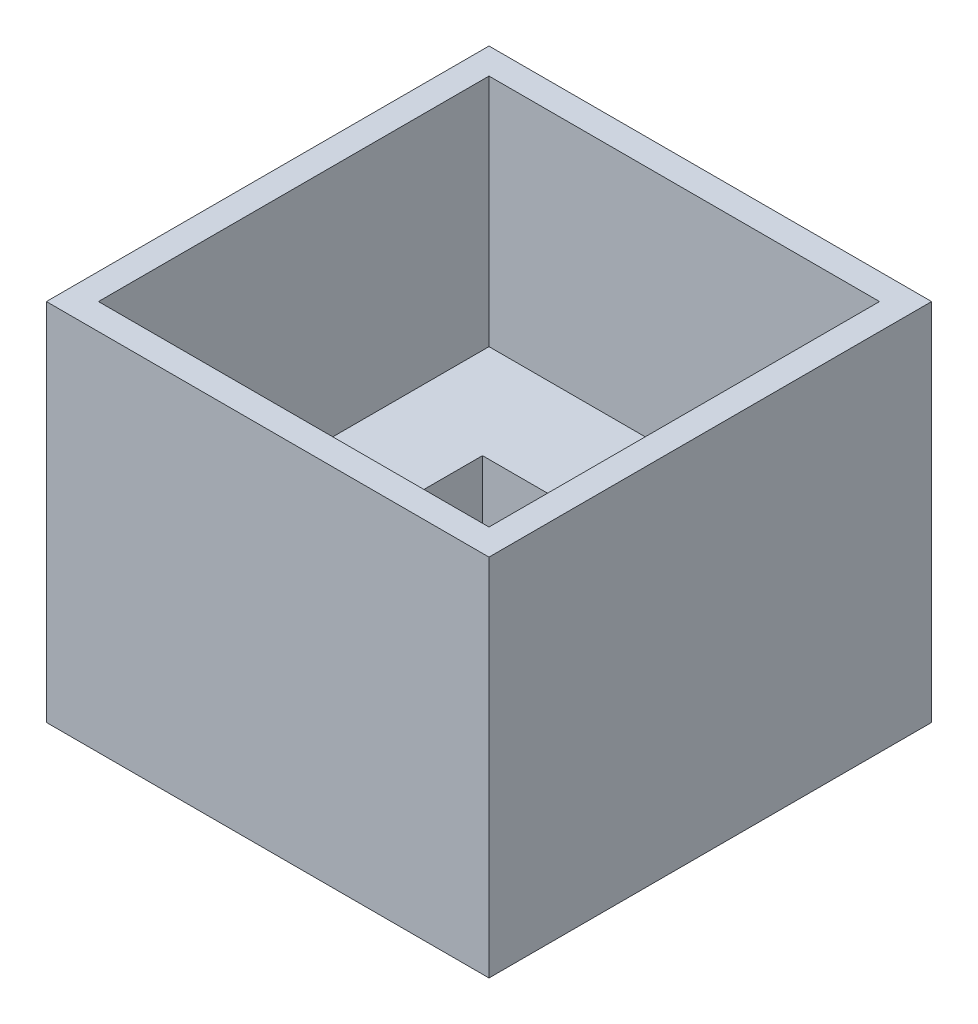
SolidWorks part; units mm, degrees
ref_plane "Front" through (0, 0, 0) normal (0, 0, 1) x (1, 0, 0)
ref_plane "Top" through (0, 0, 0) normal (0, 1, 0) x (1, 0, 0)
ref_plane "Right" through (0, 0, 0) normal (1, 0, 0) x (0, 0, -1)
sketch "Эскиз2" plane through (0, 0, 0) normal (0, 1, 0) x (1, 0, 0)
  line L1 (-85, -85) -> (85, -85)
  line L2 (-85, -85) -> (-85, 85)
  line L3 (-85, 85) -> (85, 85)
  line L4 (85, -85) -> (85, 85)
  line L5 (-85, -85) -> (85, 85) construction
  line L6 (-85, 85) -> (85, -85) construction
  point P0 (0, 0)
extrude "Бобышка-Вытянуть1" add sketch "Эскиз2" along normal blind 140
sketch "Эскиз3" plane through (0, 140, 0) normal (0, 1, 0) x (1, 0, 0)
  line L1 (-75, -75) -> (75, -75)
  line L2 (-75, -75) -> (-75, 75)
  line L3 (-75, 75) -> (75, 75)
  line L4 (75, -75) -> (75, 75)
  line L5 (-75, -75) -> (75, 75) construction
  line L6 (-75, 75) -> (75, -75) construction
  point P0 (0, 0)
extrude "Вырез-Вытянуть1" cut sketch "Эскиз3" against normal blind 90
sketch "Эскиз4" plane through (0, 50, 0) normal (0, 1, 0) x (1, 0, 0)
  line L1 (-40, 37.5) -> (40, 37.5)
  line L2 (-40, 37.5) -> (-40, -37.5)
  line L3 (-40, -37.5) -> (40, -37.5)
  line L4 (40, 37.5) -> (40, -37.5)
  line L5 (-40, 37.5) -> (40, -37.5) construction
  line L6 (-40, -37.5) -> (40, 37.5) construction
  point P0 (0, 0)
extrude "Вырез-Вытянуть2" cut sketch "Эскиз4" against normal up to next
